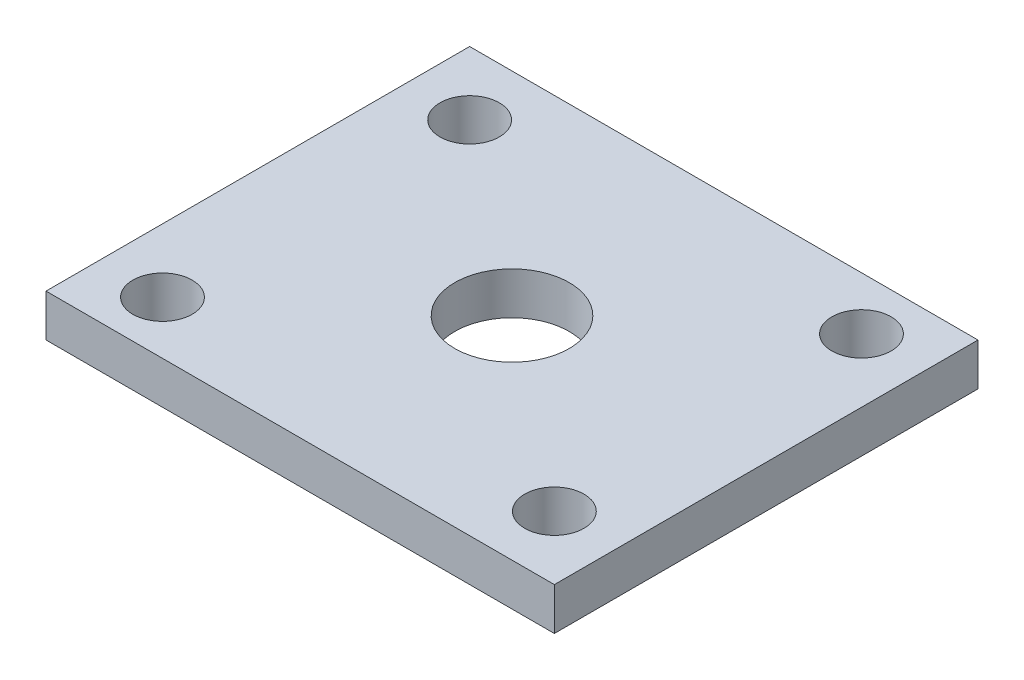
SolidWorks part; units mm, degrees
ref_plane "前视基准面" through (0, 0, 0) normal (0, 0, 1) x (1, 0, 0)
ref_plane "上视基准面" through (0, 0, 0) normal (0, 1, 0) x (1, 0, 0)
ref_plane "右视基准面" through (0, 0, 0) normal (1, 0, 0) x (0, 0, -1)
other "Configuration Table"
sketch "草图1" plane through (0, 0, 0) normal (0, 1, 0) x (1, 0, 0)
  line L1 (-6, 5) -> (6, 5)
  line L2 (-6, 5) -> (-6, -5)
  line L3 (-6, -5) -> (6, -5)
  line L4 (6, 5) -> (6, -5)
  line L5 (-6, 5) -> (6, -5) construction
  line L6 (-6, -5) -> (6, 5) construction
  line L7 (-3, 3) -> (3, 3)
  line L8 (-3, 3) -> (-3, -3)
  line L9 (-3, -3) -> (3, -3)
  line L10 (3, 3) -> (3, -3)
  line L11 (-3, 3) -> (3, -3) construction
  line L12 (-3, -3) -> (3, 3) construction
  circle A0 centre (0, 0) radius 1.35
  circle A1 centre (-4.5, 3.5) radius 0.7
  circle A2 centre (4.5, -3.5) radius 0.7
  circle A3 centre (4.5, 3.75) radius 0.7
  circle A4 centre (-4.5, -3.75) radius 0.7
  point P0 (0, 0)
  point P5 (0, 0)
  point P13 (0, 0)
  point P14 (0, 0)
  point P22 (0, 0)
  dimension "D1" = 2.7
  dimension "D4" = 1.4
  dimension "D2" = 6
  dimension "D3" = 10
  dimension "D5" = 12
  dimension "D6" = 1.5
  dimension "D7" = 1.5
  dimension "D8" = 1.5
  dimension "D9" = 1.5
extrude "凸台-拉伸1" add sketch "草图1" along normal blind 1
